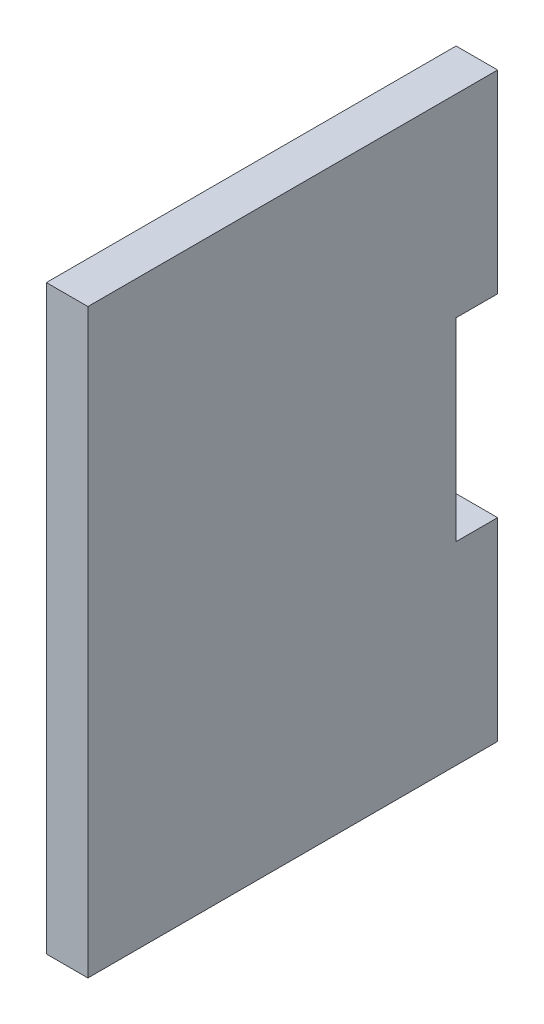
SolidWorks part; units mm, degrees
ref_plane "Front Plane" through (0, 0, 0) normal (0, 0, 1) x (1, 0, 0)
ref_plane "Top Plane" through (0, 0, 0) normal (0, 1, 0) x (1, 0, 0)
ref_plane "Right Plane" through (0, 0, 0) normal (1, 0, 0) x (0, 0, -1)
sketch "Sketch1" plane through (0, 0, 0) normal (1, 0, 0) x (0, 0, -1)
  line L1 (0, 0) -> (28.1432, 0)
  line L2 (0, 0) -> (0, 44.45)
  line L3 (0, 44.45) -> (28.1432, 44.45)
  line L4 (28.1432, 0) -> (28.1432, 44.45)
  line L5 (28.1432, 44.45) -> (31.3182, 44.45)
  line L6 (28.1432, 44.45) -> (28.1432, 29.6333)
  line L7 (28.1432, 29.6333) -> (31.3182, 29.6333)
  line L8 (31.3182, 44.45) -> (31.3182, 29.6333)
  line L9 (28.1432, 0) -> (31.3182, 0)
  line L10 (28.1432, 0) -> (28.1432, 14.8167)
  line L11 (28.1432, 14.8167) -> (31.3182, 14.8167)
  line L12 (31.3182, 0) -> (31.3182, 14.8167)
  dimension "D1" = 28.1432
  dimension "D2" = 44.45
  dimension "D3" = 3.175
  dimension "D4" = 14.8167
  dimension "D5" = 14.8167
extrude "Boss-Extrude1" add sketch "Sketch1" along normal blind 3.175 contours L1 L4 L3 L2 | L8 L5 L4 L7 | L9 L12 L11 L4
